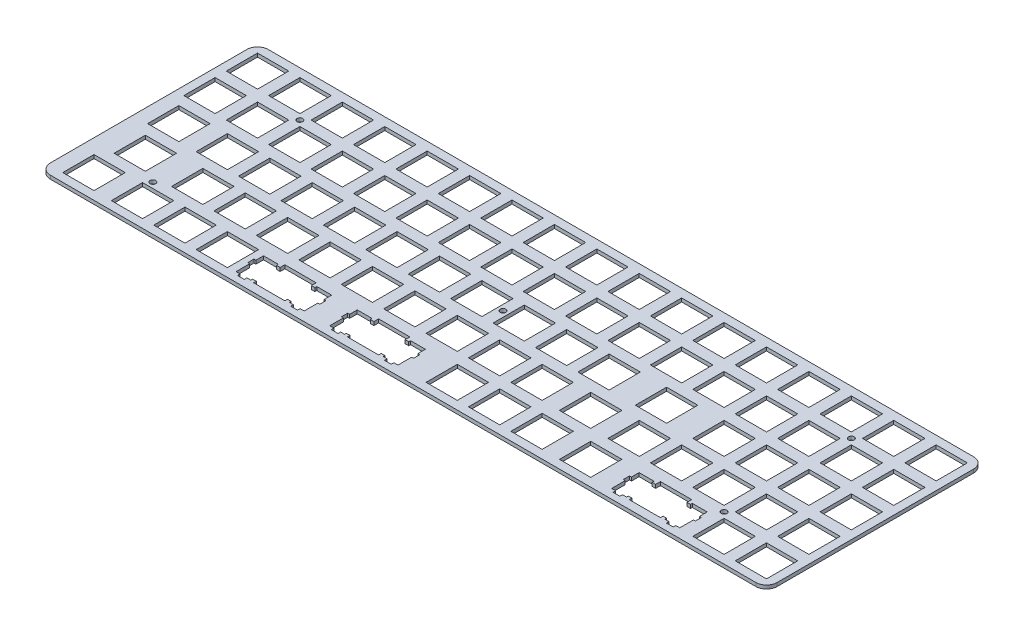
SolidWorks part; units mm, degrees
ref_plane "Front Plane" through (0, 0, 0) normal (0, 0, 1) x (1, 0, 0)
ref_plane "Top Plane" through (0, 0, 0) normal (0, 1, 0) x (1, 0, 0)
ref_plane "Right Plane" through (0, 0, 0) normal (1, 0, 0) x (0, 0, -1)
sketch "Sketch2" plane through (0, 0, 0) normal (0, 1, 0) x (1, 0, 0)
  line L0 (132.2523, -59.0023) -> (132.2523, -61.1232)
  line L1 (81.9846, -63.714) -> (81.121, -63.714)
  line L2 (90.2523, -71.8166) -> (90.2523, -72.9977)
  line L3 (146.2477, -61.1232) -> (146.2477, -59.0023)
  line L4 (107.664, -72.604) -> (107.664, -73.7724)
  line L5 (130.6394, -60.3104) -> (123.9846, -60.3104)
  line L6 (110.712, -73.7724) -> (110.712, -72.604)
  line L7 (83.788, -72.604) -> (83.788, -73.7724)
  line L8 (280.7654, -60.3104) -> (274.1106, -60.3104)
  line L9 (104.2477, -72.9977) -> (104.2477, -71.8166)
  line L10 (90.2523, -61.1232) -> (88.6394, -61.1232)
  line L11 (81.121, -63.714) -> (81.121, -66.508)
  line L12 (149.664, -73.7724) -> (152.712, -73.7724)
  line L13 (110.712, -72.604) -> (112.5154, -72.604)
  line L14 (274.1106, -60.3104) -> (274.1106, -61.1232)
  line L15 (83.788, -73.7724) -> (86.836, -73.7724)
  line L16 (112.5154, -66.508) -> (113.379, -66.508)
  line L17 (88.6394, -72.604) -> (88.6394, -71.8166)
  line L18 (123.9846, -72.604) -> (125.788, -72.604)
  line L19 (255.086, -73.7724) -> (255.086, -72.604)
  line L20 (280.7654, -63.714) -> (280.7654, -60.3104)
  line L21 (105.8606, -72.604) -> (107.664, -72.604)
  line L22 (88.6394, -60.3104) -> (81.9846, -60.3104)
  line L23 (112.5154, -63.714) -> (112.5154, -60.3104)
  line L24 (258.5023, -72.9977) -> (272.4977, -72.9977)
  line L25 (258.5023, -71.8166) -> (258.5023, -72.9977)
  line L26 (53.9977, 3.0023) -> (53.9977, 16.9977)
  line L27 (281.629, -66.508) -> (281.629, -63.714)
  line L28 (252.038, -73.7724) -> (255.086, -73.7724)
  line L29 (81.9846, -60.3104) -> (81.9846, -63.714)
  line L30 (86.836, -73.7724) -> (86.836, -72.604)
  line L31 (249.371, -66.508) -> (250.2346, -66.508)
  line L32 (104.2477, -61.1232) -> (104.2477, -59.0023)
  line L33 (81.9846, -66.508) -> (81.9846, -72.604)
  line L34 (146.2477, -59.0023) -> (132.2523, -59.0023)
  line L35 (256.8894, -71.8166) -> (258.5023, -71.8166)
  line L36 (81.9846, -72.604) -> (83.788, -72.604)
  line L37 (112.5154, -72.604) -> (112.5154, -66.508)
  line L38 (275.914, -73.7724) -> (278.962, -73.7724)
  line L39 (88.6394, -71.8166) -> (90.2523, -71.8166)
  line L40 (2.0023, 16.9977) -> (2.0023, 3.0023)
  line L41 (123.9846, -66.508) -> (123.9846, -72.604)
  line L42 (154.5154, -63.714) -> (154.5154, -60.3104)
  line L43 (86.836, -72.604) -> (88.6394, -72.604)
  line L44 (278.962, -73.7724) -> (278.962, -72.604)
  line L45 (90.2523, -59.0023) -> (90.2523, -61.1232)
  line L46 (107.664, -73.7724) -> (110.712, -73.7724)
  line L47 (272.4977, -61.1232) -> (272.4977, -59.0023)
  line L48 (104.2477, -59.0023) -> (90.2523, -59.0023)
  line L49 (255.086, -72.604) -> (256.8894, -72.604)
  line L50 (90.2523, -72.9977) -> (104.2477, -72.9977)
  line L51 (280.7654, -72.604) -> (280.7654, -66.508)
  line L52 (105.8606, -61.1232) -> (104.2477, -61.1232)
  line L53 (105.8606, -60.3104) -> (105.8606, -61.1232)
  line L54 (272.4977, -72.9977) -> (272.4977, -71.8166)
  line L55 (21.0023, 3.0023) -> (34.9977, 3.0023)
  line L56 (275.914, -72.604) -> (275.914, -73.7724)
  line L57 (256.8894, -72.604) -> (256.8894, -71.8166)
  line L58 (88.6394, -61.1232) -> (88.6394, -60.3104)
  line L59 (113.379, -63.714) -> (112.5154, -63.714)
  line L60 (15.9977, 3.0023) -> (15.9977, 16.9977)
  line L61 (258.5023, -59.0023) -> (258.5023, -61.1232)
  line L62 (274.1106, -72.604) -> (275.914, -72.604)
  line L63 (112.5154, -60.3104) -> (105.8606, -60.3104)
  line L64 (319.9977, -34.9977) -> (319.9977, -21.0023)
  line L65 (306.0023, -53.9977) -> (319.9977, -53.9977)
  line L66 (205.5023, -72.9977) -> (219.4977, -72.9977)
  line L67 (287.0023, -21.0023) -> (287.0023, -34.9977)
  line L68 (110.5023, -53.9977) -> (124.4977, -53.9977)
  line L69 (300.9977, -34.9977) -> (300.9977, -21.0023)
  line L70 (300.9977, -59.0023) -> (287.0023, -59.0023)
  line L71 (192.4977, -21.0023) -> (178.5023, -21.0023)
  line L72 (306.0023, -59.0023) -> (306.0023, -72.9977)
  line L73 (300.9977, -53.9977) -> (300.9977, -40.0023)
  line L74 (300.9977, -40.0023) -> (287.0023, -40.0023)
  line L75 (268.0023, -53.9977) -> (281.9977, -53.9977)
  line L76 (268.0023, -21.0023) -> (268.0023, -34.9977)
  line L77 (319.9977, -72.9977) -> (319.9977, -59.0023)
  line L78 (167.5023, -53.9977) -> (181.4977, -53.9977)
  line L79 (319.9977, -21.0023) -> (306.0023, -21.0023)
  line L80 (287.0023, -53.9977) -> (300.9977, -53.9977)
  line L81 (278.962, -72.604) -> (280.7654, -72.604)
  line L82 (287.0023, -72.9977) -> (300.9977, -72.9977)
  line L83 (300.9977, -21.0023) -> (287.0023, -21.0023)
  line L84 (319.9977, -40.0023) -> (306.0023, -40.0023)
  line L85 (300.9977, -72.9977) -> (300.9977, -59.0023)
  line L86 (274.1106, -71.8166) -> (274.1106, -72.604)
  line L87 (281.9977, -40.0023) -> (268.0023, -40.0023)
  line L88 (287.0023, -34.9977) -> (300.9977, -34.9977)
  line L89 (274.1106, -61.1232) -> (272.4977, -61.1232)
  line L90 (287.0023, -59.0023) -> (287.0023, -72.9977)
  line L91 (178.5023, -34.9977) -> (192.4977, -34.9977)
  line L92 (249.0023, -21.0023) -> (249.0023, -34.9977)
  line L93 (306.0023, -72.9977) -> (319.9977, -72.9977)
  line L94 (306.0023, -21.0023) -> (306.0023, -34.9977)
  line L95 (268.0023, -40.0023) -> (268.0023, -53.9977)
  line L96 (272.4977, -71.8166) -> (274.1106, -71.8166)
  line L97 (287.0023, -40.0023) -> (287.0023, -53.9977)
  line L98 (262.9977, -21.0023) -> (249.0023, -21.0023)
  line L99 (110.5023, -40.0023) -> (110.5023, -53.9977)
  line L100 (268.0023, -34.9977) -> (281.9977, -34.9977)
  line L101 (281.9977, -34.9977) -> (281.9977, -21.0023)
  line L102 (200.4977, -53.9977) -> (200.4977, -40.0023)
  line L103 (319.9977, -59.0023) -> (306.0023, -59.0023)
  line L104 (306.0023, -34.9977) -> (319.9977, -34.9977)
  line L105 (319.9977, -53.9977) -> (319.9977, -40.0023)
  line L106 (281.629, -63.714) -> (280.7654, -63.714)
  line L107 (281.9977, -21.0023) -> (268.0023, -21.0023)
  line L108 (281.9977, -53.9977) -> (281.9977, -40.0023)
  line L109 (135.4977, -21.0023) -> (121.5023, -21.0023)
  line L110 (306.0023, -40.0023) -> (306.0023, -53.9977)
  line L111 (200.4977, -72.9977) -> (200.4977, -59.0023)
  line L112 (249.0023, -34.9977) -> (262.9977, -34.9977)
  line L113 (162.4977, -53.9977) -> (162.4977, -40.0023)
  line L114 (249.0023, -40.0023) -> (249.0023, -53.9977)
  line L115 (181.4977, -40.0023) -> (167.5023, -40.0023)
  line L116 (148.5023, -53.9977) -> (162.4977, -53.9977)
  line L117 (167.5023, -40.0023) -> (167.5023, -53.9977)
  line L118 (148.5023, -40.0023) -> (148.5023, -53.9977)
  line L119 (129.5023, -53.9977) -> (143.4977, -53.9977)
  line L120 (262.9977, -53.9977) -> (262.9977, -40.0023)
  line L121 (129.5023, -40.0023) -> (129.5023, -53.9977)
  line L122 (124.4977, -53.9977) -> (124.4977, -40.0023)
  line L123 (262.9977, -34.9977) -> (262.9977, -21.0023)
  line L124 (186.5023, -59.0023) -> (186.5023, -72.9977)
  line L125 (4.7523, -59.0023) -> (4.7523, -72.9977)
  line L126 (181.4977, -53.9977) -> (181.4977, -40.0023)
  line L127 (205.5023, -59.0023) -> (205.5023, -72.9977)
  line L128 (230.0023, -53.9977) -> (243.9977, -53.9977)
  line L129 (162.4977, -40.0023) -> (148.5023, -40.0023)
  line L130 (121.5023, -21.0023) -> (121.5023, -34.9977)
  line L131 (45.5023, -59.0023) -> (45.5023, -72.9977)
  line L132 (140.5023, -34.9977) -> (154.4977, -34.9977)
  line L133 (135.4977, -34.9977) -> (135.4977, -21.0023)
  line L134 (45.5023, -34.9977) -> (59.4977, -34.9977)
  line L135 (97.4977, -21.0023) -> (83.5023, -21.0023)
  line L136 (237.2477, -21.0023) -> (223.2523, -21.0023)
  line L137 (200.4977, -40.0023) -> (186.5023, -40.0023)
  line L138 (178.5023, -21.0023) -> (178.5023, -34.9977)
  line L139 (211.4977, -34.9977) -> (211.4977, -21.0023)
  line L140 (154.4977, -34.9977) -> (154.4977, -21.0023)
  line L141 (186.5023, -40.0023) -> (186.5023, -53.9977)
  line L142 (121.5023, -34.9977) -> (135.4977, -34.9977)
  line L143 (78.4977, -59.0023) -> (64.5023, -59.0023)
  line L144 (72.5023, -40.0023) -> (72.5023, -53.9977)
  line L145 (173.4977, -34.9977) -> (173.4977, -21.0023)
  line L146 (159.5023, -21.0023) -> (159.5023, -34.9977)
  line L147 (200.4977, -59.0023) -> (186.5023, -59.0023)
  line L148 (192.4977, -34.9977) -> (192.4977, -21.0023)
  line L149 (143.4977, -40.0023) -> (129.5023, -40.0023)
  line L150 (249.0023, -53.9977) -> (262.9977, -53.9977)
  line L151 (124.4977, -40.0023) -> (110.5023, -40.0023)
  line L152 (59.4977, -72.9977) -> (59.4977, -59.0023)
  line L153 (143.4977, -53.9977) -> (143.4977, -40.0023)
  line L154 (140.5023, -21.0023) -> (140.5023, -34.9977)
  line L155 (64.5023, -72.9977) -> (78.4977, -72.9977)
  line L156 (197.5023, -34.9977) -> (211.4977, -34.9977)
  line L157 (48.4977, -40.0023) -> (34.5023, -40.0023)
  line L158 (154.4977, -21.0023) -> (140.5023, -21.0023)
  line L159 (219.4977, -72.9977) -> (219.4977, -59.0023)
  line L160 (173.4977, -21.0023) -> (159.5023, -21.0023)
  line L161 (45.5023, -72.9977) -> (59.4977, -72.9977)
  line L162 (208.2523, -40.0023) -> (208.2523, -53.9977)
  line L163 (223.2523, -34.9977) -> (237.2477, -34.9977)
  line L164 (159.5023, -34.9977) -> (173.4977, -34.9977)
  line L165 (8.7523, -53.9977) -> (22.7477, -53.9977)
  line L166 (186.5023, -53.9977) -> (200.4977, -53.9977)
  line L167 (59.4977, -59.0023) -> (45.5023, -59.0023)
  line L168 (219.4977, -59.0023) -> (205.5023, -59.0023)
  line L169 (262.9977, -40.0023) -> (249.0023, -40.0023)
  line L170 (78.4977, -72.9977) -> (78.4977, -59.0023)
  line L171 (186.5023, -72.9977) -> (200.4977, -72.9977)
  line L172 (211.4977, -21.0023) -> (197.5023, -21.0023)
  line L173 (64.5023, -59.0023) -> (64.5023, -72.9977)
  line L174 (197.5023, -21.0023) -> (197.5023, -34.9977)
  line L175 (97.0023, -15.9977) -> (110.9977, -15.9977)
  line L176 (167.5023, -59.0023) -> (167.5023, -72.9977)
  line L177 (8.7523, -40.0023) -> (8.7523, -53.9977)
  line L178 (167.9977, -2.0023) -> (154.0023, -2.0023)
  line L179 (40.4977, -21.0023) -> (26.5023, -21.0023)
  line L180 (86.4977, -53.9977) -> (86.4977, -40.0023)
  line L181 (105.4977, -53.9977) -> (105.4977, -40.0023)
  line L182 (67.4977, -40.0023) -> (53.5023, -40.0023)
  line L183 (243.9977, -40.0023) -> (230.0023, -40.0023)
  line L184 (167.5023, -72.9977) -> (181.4977, -72.9977)
  line L185 (83.5023, -21.0023) -> (83.5023, -34.9977)
  line L186 (53.5023, -53.9977) -> (67.4977, -53.9977)
  line L187 (4.7523, -72.9977) -> (18.7477, -72.9977)
  line L188 (241.2477, -59.0023) -> (227.2523, -59.0023)
  line L189 (268.0023, -2.0023) -> (268.0023, -15.9977)
  line L190 (59.4977, -34.9977) -> (59.4977, -21.0023)
  line L191 (83.5023, -34.9977) -> (97.4977, -34.9977)
  line L192 (243.9977, -53.9977) -> (243.9977, -40.0023)
  line L193 (26.5023, -72.9977) -> (40.4977, -72.9977)
  line L194 (105.4977, -40.0023) -> (91.5023, -40.0023)
  line L195 (64.5023, -34.9977) -> (78.4977, -34.9977)
  line L196 (116.4977, -34.9977) -> (116.4977, -21.0023)
  line L197 (222.2477, -53.9977) -> (222.2477, -40.0023)
  line L198 (205.9977, -15.9977) -> (205.9977, -2.0023)
  line L199 (45.5023, -21.0023) -> (45.5023, -34.9977)
  line L200 (67.4977, -53.9977) -> (67.4977, -40.0023)
  line L201 (110.9977, -15.9977) -> (110.9977, -2.0023)
  line L202 (208.2523, -53.9977) -> (222.2477, -53.9977)
  line L203 (91.9977, -2.0023) -> (78.0023, -2.0023)
  line L204 (72.9977, -15.9977) -> (72.9977, -2.0023)
  line L205 (237.2477, -34.9977) -> (237.2477, -21.0023)
  line L206 (102.5023, -34.9977) -> (116.4977, -34.9977)
  line L207 (230.0023, -40.0023) -> (230.0023, -53.9977)
  line L208 (53.5023, -40.0023) -> (53.5023, -53.9977)
  line L209 (223.2523, -21.0023) -> (223.2523, -34.9977)
  line L210 (26.5023, -59.0023) -> (26.5023, -72.9977)
  line L211 (227.2523, -59.0023) -> (227.2523, -72.9977)
  line L212 (227.2523, -72.9977) -> (241.2477, -72.9977)
  line L213 (116.4977, -21.0023) -> (102.5023, -21.0023)
  line L214 (241.2477, -72.9977) -> (241.2477, -59.0023)
  line L215 (97.4977, -34.9977) -> (97.4977, -21.0023)
  line L216 (91.5023, -53.9977) -> (105.4977, -53.9977)
  line L217 (91.5023, -40.0023) -> (91.5023, -53.9977)
  line L218 (78.4977, -21.0023) -> (64.5023, -21.0023)
  line L219 (78.4977, -34.9977) -> (78.4977, -21.0023)
  line L220 (78.0023, -2.0023) -> (78.0023, -15.9977)
  line L221 (18.7477, -59.0023) -> (4.7523, -59.0023)
  line L222 (72.5023, -53.9977) -> (86.4977, -53.9977)
  line L223 (222.2477, -40.0023) -> (208.2523, -40.0023)
  line L224 (64.5023, -21.0023) -> (64.5023, -34.9977)
  line L225 (48.4977, -53.9977) -> (48.4977, -40.0023)
  line L226 (22.7477, -53.9977) -> (22.7477, -40.0023)
  line L227 (18.7477, -72.9977) -> (18.7477, -59.0023)
  line L228 (181.4977, -59.0023) -> (167.5023, -59.0023)
  line L229 (181.4977, -72.9977) -> (181.4977, -59.0023)
  line L230 (59.4977, -21.0023) -> (45.5023, -21.0023)
  line L231 (22.7477, -40.0023) -> (8.7523, -40.0023)
  line L232 (102.5023, -21.0023) -> (102.5023, -34.9977)
  line L233 (40.4977, -59.0023) -> (26.5023, -59.0023)
  line L234 (34.5023, -53.9977) -> (48.4977, -53.9977)
  line L235 (34.5023, -40.0023) -> (34.5023, -53.9977)
  line L236 (224.9977, -2.0023) -> (211.0023, -2.0023)
  line L237 (86.4977, -40.0023) -> (72.5023, -40.0023)
  line L238 (40.4977, -72.9977) -> (40.4977, -59.0023)
  line L239 (224.9977, -15.9977) -> (224.9977, -2.0023)
  line L240 (287.0023, -2.0023) -> (287.0023, -15.9977)
  line L241 (135.0023, -2.0023) -> (135.0023, -15.9977)
  line L242 (26.5023, -21.0023) -> (26.5023, -34.9977)
  line L243 (173.0023, -15.9977) -> (186.9977, -15.9977)
  line L244 (211.0023, -2.0023) -> (211.0023, -15.9977)
  line L245 (135.0023, -15.9977) -> (148.9977, -15.9977)
  line L246 (306.0023, -2.0023) -> (306.0023, -15.9977)
  line L247 (91.9977, 3.0023) -> (91.9977, 16.9977)
  line L248 (268.0023, -15.9977) -> (281.9977, -15.9977)
  line L249 (2.0023, -2.0023) -> (2.0023, -15.9977)
  line L250 (243.9977, -15.9977) -> (243.9977, -2.0023)
  line L251 (110.9977, -2.0023) -> (97.0023, -2.0023)
  line L252 (40.4977, -34.9977) -> (40.4977, -21.0023)
  line L253 (192.0023, -15.9977) -> (205.9977, -15.9977)
  line L254 (116.0023, 16.9977) -> (116.0023, 3.0023)
  line L255 (97.0023, -2.0023) -> (97.0023, -15.9977)
  line L256 (249.0023, 3.0023) -> (262.9977, 3.0023)
  line L257 (319.9977, -2.0023) -> (306.0023, -2.0023)
  line L258 (72.9977, -2.0023) -> (59.0023, -2.0023)
  line L259 (173.0023, -2.0023) -> (173.0023, -15.9977)
  line L260 (129.9977, -2.0023) -> (116.0023, -2.0023)
  line L261 (262.9977, -15.9977) -> (262.9977, -2.0023)
  line L262 (306.0023, -15.9977) -> (319.9977, -15.9977)
  line L263 (211.0023, -15.9977) -> (224.9977, -15.9977)
  line L264 (91.9977, -15.9977) -> (91.9977, -2.0023)
  line L265 (287.0023, -15.9977) -> (300.9977, -15.9977)
  line L266 (281.9977, -2.0023) -> (268.0023, -2.0023)
  line L267 (148.9977, -2.0023) -> (135.0023, -2.0023)
  line L268 (281.9977, -15.9977) -> (281.9977, -2.0023)
  line L269 (300.9977, -15.9977) -> (300.9977, -2.0023)
  line L270 (243.9977, -2.0023) -> (230.0023, -2.0023)
  line L271 (72.9977, 3.0023) -> (72.9977, 16.9977)
  line L272 (319.9977, -15.9977) -> (319.9977, -2.0023)
  line L273 (2.0023, -15.9977) -> (15.9977, -15.9977)
  line L274 (186.9977, -2.0023) -> (173.0023, -2.0023)
  line L275 (249.0023, -2.0023) -> (249.0023, -15.9977)
  line L276 (59.0023, 3.0023) -> (72.9977, 3.0023)
  line L277 (167.9977, -15.9977) -> (167.9977, -2.0023)
  line L278 (300.9977, -2.0023) -> (287.0023, -2.0023)
  line L279 (59.0023, -15.9977) -> (72.9977, -15.9977)
  line L280 (306.0023, 16.9977) -> (306.0023, 3.0023)
  line L281 (154.0023, -15.9977) -> (167.9977, -15.9977)
  line L282 (154.0023, -2.0023) -> (154.0023, -15.9977)
  line L283 (116.0023, -2.0023) -> (116.0023, -15.9977)
  line L284 (148.9977, -15.9977) -> (148.9977, -2.0023)
  line L285 (129.9977, -15.9977) -> (129.9977, -2.0023)
  line L286 (15.9977, -15.9977) -> (15.9977, -2.0023)
  line L287 (186.9977, -15.9977) -> (186.9977, -2.0023)
  line L288 (26.5023, -34.9977) -> (40.4977, -34.9977)
  line L289 (205.9977, -2.0023) -> (192.0023, -2.0023)
  line L290 (230.0023, -2.0023) -> (230.0023, -15.9977)
  line L291 (15.9977, -2.0023) -> (2.0023, -2.0023)
  line L292 (230.0023, -15.9977) -> (243.9977, -15.9977)
  line L293 (116.0023, -15.9977) -> (129.9977, -15.9977)
  line L294 (78.0023, -15.9977) -> (91.9977, -15.9977)
  line L295 (249.0023, -15.9977) -> (262.9977, -15.9977)
  line L296 (262.9977, -2.0023) -> (249.0023, -2.0023)
  line L297 (21.0023, -15.9977) -> (34.9977, -15.9977)
  line L298 (192.0023, -2.0023) -> (192.0023, -15.9977)
  line L299 (167.9977, 16.9977) -> (154.0023, 16.9977)
  line L300 (154.5154, -72.604) -> (154.5154, -66.508)
  line L301 (205.9977, 16.9977) -> (192.0023, 16.9977)
  line L302 (59.0023, -2.0023) -> (59.0023, -15.9977)
  line L303 (249.0023, 16.9977) -> (249.0023, 3.0023)
  line L304 (129.9977, 16.9977) -> (116.0023, 16.9977)
  line L305 (306.0023, 3.0023) -> (319.9977, 3.0023)
  line L306 (224.9977, 3.0023) -> (224.9977, 16.9977)
  line L307 (224.9977, 16.9977) -> (211.0023, 16.9977)
  line L308 (154.0023, 3.0023) -> (167.9977, 3.0023)
  line L309 (300.9977, 3.0023) -> (300.9977, 16.9977)
  line L310 (135.0023, 16.9977) -> (135.0023, 3.0023)
  line L311 (173.0023, 3.0023) -> (186.9977, 3.0023)
  line L312 (287.0023, 16.9977) -> (287.0023, 3.0023)
  line L313 (34.9977, 16.9977) -> (21.0023, 16.9977)
  line L314 (2.0023, 3.0023) -> (15.9977, 3.0023)
  line L315 (149.664, -72.604) -> (149.664, -73.7724)
  line L316 (59.0023, 16.9977) -> (59.0023, 3.0023)
  line L317 (287.0023, 3.0023) -> (300.9977, 3.0023)
  line L318 (281.9977, 3.0023) -> (281.9977, 16.9977)
  line L319 (97.0023, 16.9977) -> (97.0023, 3.0023)
  line L320 (78.0023, 16.9977) -> (78.0023, 3.0023)
  line L321 (40.0023, -2.0023) -> (40.0023, -15.9977)
  line L322 (262.9977, 16.9977) -> (249.0023, 16.9977)
  line L323 (154.5154, -66.508) -> (155.379, -66.508)
  line L324 (323.778, -72.0155) -> (323.778, 16.0155)
  line L325 (148.9977, 3.0023) -> (148.9977, 16.9977)
  line L326 (154.0023, 16.9977) -> (154.0023, 3.0023)
  line L327 (146.2477, -72.9977) -> (146.2477, -71.8166)
  line L328 (256.8894, -60.3104) -> (250.2346, -60.3104)
  line L329 (40.0023, -15.9977) -> (53.9977, -15.9977)
  line L330 (53.9977, -2.0023) -> (40.0023, -2.0023)
  line L331 (192.0023, 16.9977) -> (192.0023, 3.0023)
  line L332 (155.379, -63.714) -> (154.5154, -63.714)
  line L333 (91.9977, 16.9977) -> (78.0023, 16.9977)
  line L334 (211.0023, 16.9977) -> (211.0023, 3.0023)
  line L335 (300.9977, 16.9977) -> (287.0023, 16.9977)
  line L336 (173.0023, 16.9977) -> (173.0023, 3.0023)
  line L337 (78.0023, 3.0023) -> (91.9977, 3.0023)
  line L338 (262.9977, 3.0023) -> (262.9977, 16.9977)
  line L339 (97.0023, 3.0023) -> (110.9977, 3.0023)
  line L340 (167.9977, 3.0023) -> (167.9977, 16.9977)
  line L341 (230.0023, 16.9977) -> (230.0023, 3.0023)
  line L342 (243.9977, 16.9977) -> (230.0023, 16.9977)
  line L343 (192.0023, 3.0023) -> (205.9977, 3.0023)
  line L344 (268.0023, 3.0023) -> (281.9977, 3.0023)
  line L345 (211.0023, 3.0023) -> (224.9977, 3.0023)
  line L346 (135.0023, 3.0023) -> (148.9977, 3.0023)
  line L347 (129.9977, 3.0023) -> (129.9977, 16.9977)
  line L348 (186.9977, 16.9977) -> (173.0023, 16.9977)
  line L349 (34.9977, -15.9977) -> (34.9977, -2.0023)
  line L350 (110.9977, 16.9977) -> (97.0023, 16.9977)
  line L351 (230.0023, 3.0023) -> (243.9977, 3.0023)
  line L352 (281.9977, 16.9977) -> (268.0023, 16.9977)
  line L353 (53.9977, -15.9977) -> (53.9977, -2.0023)
  line L354 (250.2346, -66.508) -> (250.2346, -72.604)
  line L355 (186.9977, 3.0023) -> (186.9977, 16.9977)
  line L356 (72.9977, 16.9977) -> (59.0023, 16.9977)
  line L357 (110.9977, 3.0023) -> (110.9977, 16.9977)
  line L358 (21.0023, -2.0023) -> (21.0023, -15.9977)
  line L359 (148.9977, 16.9977) -> (135.0023, 16.9977)
  line L360 (243.9977, 3.0023) -> (243.9977, 16.9977)
  line L361 (116.0023, 3.0023) -> (129.9977, 3.0023)
  line L362 (205.9977, 3.0023) -> (205.9977, 16.9977)
  line L363 (319.9977, 3.0023) -> (319.9977, 16.9977)
  line L364 (34.9977, -2.0023) -> (21.0023, -2.0023)
  line L365 (319.9977, 16.9977) -> (306.0023, 16.9977)
  line L366 (268.0023, 16.9977) -> (268.0023, 3.0023)
  line L367 (147.8606, -72.604) -> (149.664, -72.604)
  line L368 (123.121, -63.714) -> (123.121, -66.508)
  line L369 (81.121, -66.508) -> (81.9846, -66.508)
  line L370 (40.0023, 3.0023) -> (53.9977, 3.0023)
  line L371 (256.8894, -61.1232) -> (256.8894, -60.3104)
  line L372 (130.6394, -61.1232) -> (130.6394, -60.3104)
  line L373 (132.2523, -71.8166) -> (132.2523, -72.9977)
  line L374 (18.7477, -34.9977) -> (18.7477, -21.0023)
  line L375 (152.712, -72.604) -> (154.5154, -72.604)
  line L376 (-1.778, 16.0155) -> (-1.778, -72.0155)
  line L377 (258.5023, -61.1232) -> (256.8894, -61.1232)
  line L378 (18.7477, -21.0023) -> (4.7523, -21.0023)
  line L379 (123.121, -66.508) -> (123.9846, -66.508)
  line L380 (128.836, -73.7724) -> (128.836, -72.604)
  line L381 (34.9977, 3.0023) -> (34.9977, 16.9977)
  line L382 (250.2346, -72.604) -> (252.038, -72.604)
  line L383 (40.0023, 16.9977) -> (40.0023, 3.0023)
  line L384 (272.4977, -59.0023) -> (258.5023, -59.0023)
  line L385 (280.7654, -66.508) -> (281.629, -66.508)
  line L386 (130.6394, -71.8166) -> (132.2523, -71.8166)
  line L387 (250.2346, -60.3104) -> (250.2346, -63.714)
  line L388 (21.0023, 16.9977) -> (21.0023, 3.0023)
  line L389 (123.9846, -63.714) -> (123.121, -63.714)
  line L390 (125.788, -72.604) -> (125.788, -73.7724)
  line L391 (123.9846, -60.3104) -> (123.9846, -63.714)
  line L392 (130.6394, -72.604) -> (130.6394, -71.8166)
  line L393 (4.7523, -34.9977) -> (18.7477, -34.9977)
  line L394 (125.788, -73.7724) -> (128.836, -73.7724)
  line L395 (4.7523, -21.0023) -> (4.7523, -34.9977)
  line L396 (105.8606, -71.8166) -> (105.8606, -72.604)
  line L397 (147.8606, -61.1232) -> (146.2477, -61.1232)
  line L398 (53.9977, 16.9977) -> (40.0023, 16.9977)
  line L399 (147.8606, -71.8166) -> (147.8606, -72.604)
  line L400 (152.712, -73.7724) -> (152.712, -72.604)
  line L401 (146.2477, -71.8166) -> (147.8606, -71.8166)
  line L402 (128.836, -72.604) -> (130.6394, -72.604)
  line L403 (154.5154, -60.3104) -> (147.8606, -60.3104)
  line L404 (147.8606, -60.3104) -> (147.8606, -61.1232)
  line L405 (249.371, -63.714) -> (249.371, -66.508)
  line L406 (113.379, -66.508) -> (113.379, -63.714)
  line L407 (2.9845, -76.778) -> (319.0155, -76.778)
  line L408 (104.2477, -71.8166) -> (105.8606, -71.8166)
  line L409 (155.379, -66.508) -> (155.379, -63.714)
  line L410 (250.2346, -63.714) -> (249.371, -63.714)
  line L411 (15.9977, 16.9977) -> (2.0023, 16.9977)
  line L412 (319.0155, 20.778) -> (2.9845, 20.778)
  line L413 (252.038, -72.604) -> (252.038, -73.7724)
  line L414 (132.2523, -72.9977) -> (146.2477, -72.9977)
  line L415 (132.2523, -61.1232) -> (130.6394, -61.1232)
  circle A0 centre (157, -28) radius 1.27
  circle A1 centre (37.5, 0.5) radius 1.27
  circle A2 centre (284.5, 0.5) radius 1.27
  circle A3 centre (284.5, -56.5) radius 1.27
  circle A4 centre (28.625, -56.5) radius 1.27
  arc A5 (-1.778, -72.0155) -> (2.9845, -76.778) centre (2.9845, -72.0155) ccw
  arc A6 (319.0155, -76.778) -> (323.778, -72.0155) centre (319.0155, -72.0155) ccw
  arc A7 (2.9845, 20.778) -> (-1.778, 16.0155) centre (2.9845, 16.0155) ccw
  arc A8 (323.778, 16.0155) -> (319.0155, 20.778) centre (319.0155, 16.0155) ccw
  point P3 (0, 0)
extrude "Boss-Extrude1" add sketch "Sketch2" along normal mid plane 1.5875
ref_plane "Plane1" through (161, 0, 0) normal (1, 0, 0) x (0, 0, -1)
ref_plane "Plane2" through (0, 0, 28) normal (0, 0, 1) x (1, 0, 0)
